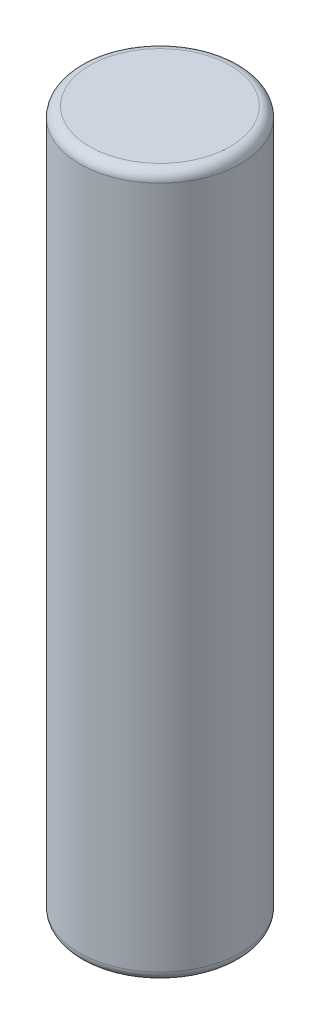
SolidWorks part; units mm, degrees
ref_plane "Front Plane" through (0, 0, 0) normal (0, 0, 1) x (1, 0, 0)
ref_plane "Top Plane" through (0, 0, 0) normal (0, 1, 0) x (1, 0, 0)
ref_plane "Right Plane" through (0, 0, 0) normal (1, 0, 0) x (0, 0, -1)
sketch "Sketch2" plane through (0, 0, 0) normal (0, 1, 0) x (1, 0, 0)
  circle A0 centre (0, 0) radius 0.8
extrude "Boss-Extrude1" add sketch "Sketch2" along normal blind 7
fillet "Fillet3" radius 0.1 2 edges at (0, 0, 0.8) (0, 7, 0.8)
